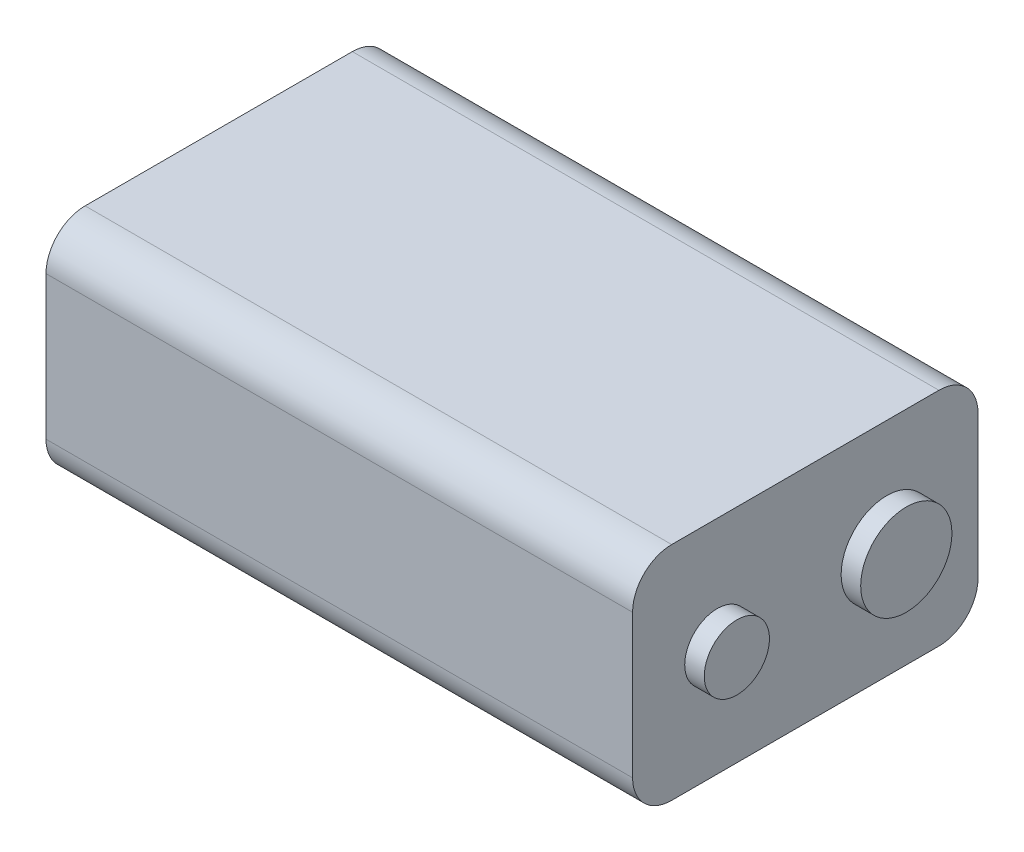
SolidWorks part; units mm, degrees
ref_plane "Front Plane" through (0, 0, 0) normal (0, 0, 1) x (1, 0, 0)
ref_plane "Top Plane" through (0, 0, 0) normal (0, 1, 0) x (1, 0, 0)
ref_plane "Right Plane" through (0, 0, 0) normal (1, 0, 0) x (0, 0, -1)
sketch "Sketch1" plane through (0, 0, 0) normal (0, 1, 0) x (1, 0, 0)
  line L1 (-21.9474, 18.298) -> (23.0526, 18.298)
  line L2 (-21.9474, 18.298) -> (-21.9474, -8.202)
  line L3 (-21.9474, -8.202) -> (23.0526, -8.202)
  line L4 (23.0526, 18.298) -> (23.0526, -8.202)
  dimension "D1" = 45
  dimension "D2" = 26.5
extrude "Boss-Extrude1" add sketch "Sketch1" along normal blind 17
fillet "Fillet1" radius 3 4 edges at (0.5526, 17, -18.298) (0.5526, 0, -18.298) (0.5526, 0, 8.202) (0.5526, 17, 8.202)
sketch "Sketch2" plane through (23.0526, 0, 0) normal (1, 0, 0) x (0, 0, -1)
  line L0 (18.298, 14) -> (18.298, 3) construction
  line L4 (-8.202, 14) -> (-8.202, 3) construction
  circle A0 centre (11.298, 8.5) radius 3.5
  circle A1 centre (-1.702, 8.5) radius 2.5
  point P7 (18.298, 8.5)
  dimension "D3" = 5
  dimension "D4" = 7
  dimension "D1" = 13
  dimension "D2" = 6.5
extrude "Boss-Extrude2" add sketch "Sketch2" along normal blind 1.5
